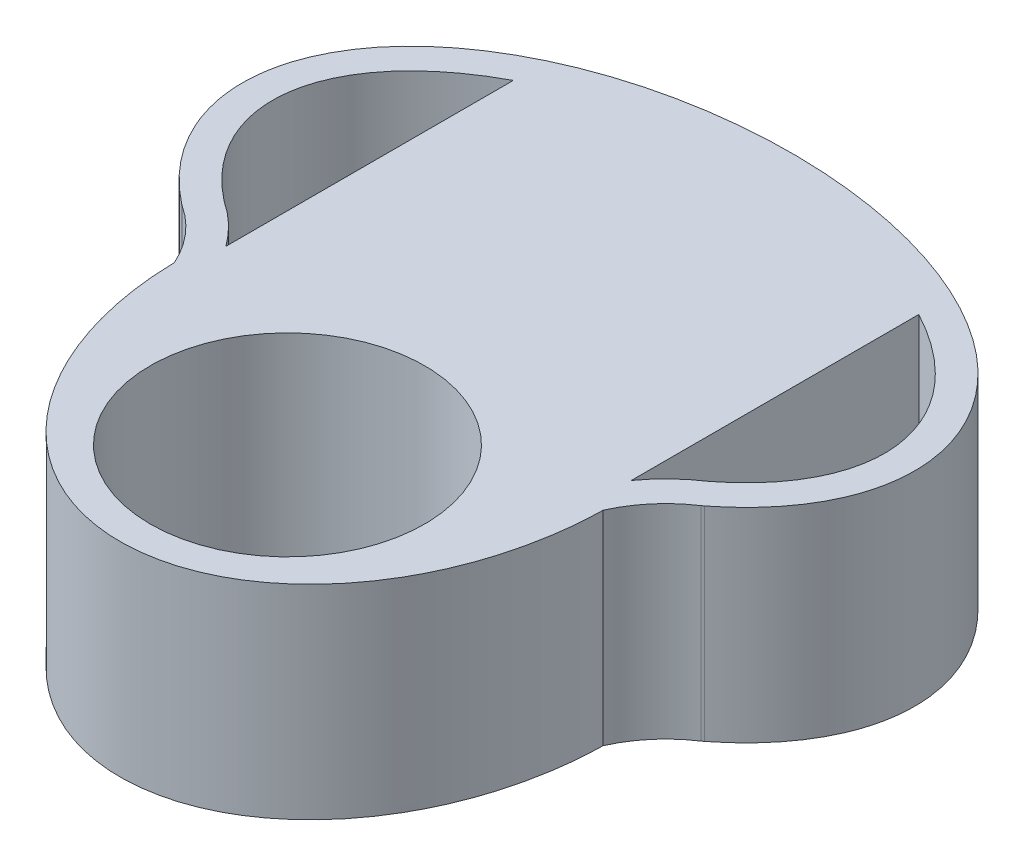
SolidWorks part; units mm, degrees
ref_plane "Front Plane" through (0, 0, 0) normal (0, 0, 1) x (1, 0, 0)
ref_plane "Top Plane" through (0, 0, 0) normal (0, 1, 0) x (1, 0, 0)
ref_plane "Right Plane" through (0, 0, 0) normal (1, 0, 0) x (0, 0, -1)
sketch "Sketch2" plane through (0, 0, 0) normal (0, 1, 0) x (1, 0, 0)
  line L0 (0, -133.35) -> (0, -153.202) construction
  line L1 (0, -153.202) -> (0, -133.35) construction
  line L2 (-81.4183, -42.1453) -> (-80.7825, -42.602)
  line L3 (81.4183, -42.1453) -> (80.7825, -42.602)
  line L6 (-63.1172, -46.6961) -> (-63.1172, 42.8014)
  line L7 (-54.373, -42.2538) -> (-54.373, 46.9235)
  line L8 (-54.373, -42.2538) -> (-54.373, -81.4864)
  line L9 (0, -260.0939) -> (0, 176.9209) construction
  line L10 (63.1172, -46.6961) -> (63.1172, 42.8014)
  line L11 (54.373, -42.2538) -> (54.373, 46.9235)
  line L12 (54.373, -42.2538) -> (54.373, -81.4864)
  line L13 (-63.1172, -46.6961) -> (63.1172, -46.6961)
  arc A0 (-57.378, -57.15) -> (-75.6222, -34.7474) centre (-101.9466, -74.8157) ccw
  arc A1 (57.378, -57.15) -> (75.6222, -34.7474) centre (101.9466, -74.8157) cw
  circle A2 centre (0, -90.6305) radius 42.7195
  arc A3 (66.759, -59.0842) -> (80.7825, -42.602) centre (101.9466, -74.8157) cw
  arc A4 (-66.759, -59.0842) -> (-80.7825, -42.602) centre (-101.9466, -74.8157) ccw
  arc A6 (66.1147, -60.613) -> (80.7825, -42.602) centre (101.9466, -74.8157) cw construction
  arc A7 (-66.1147, -60.613) -> (-80.7825, -42.602) centre (-101.9466, -74.8157) ccw construction
  ellipse E0 centre (0, 0) end of major axis (-95.25, 0) minor radius 57.15 (75.6222, -34.7474) -> (-75.6222, -34.7474) ccw
  ellipse E1 centre (0, -57.15) end of major axis (0, -133.35) minor radius 57.378 (-57.378, -57.15) -> (57.378, -57.15) ccw
  ellipse E2 centre (0, -57.15) end of major axis (0, -133.35) minor radius 57.378 (57.378, -57.15) -> (-57.378, -57.15) cw
  ellipse E3 centre (0, 0) end of major axis (95.25, 0) minor radius 57.15 (-75.6222, -34.7474) -> (75.6222, -34.7474) cw
  spline S0 degree 1 poles (-66.776, -57.15) (66.776, -57.15) knots 0 0 1 1 construction
  spline S1 degree 3 poles (-66.776, -57.15) (-66.776, -57.6322) (-66.7707, -58.4398) (-66.6753, -63.8877) (-65.7907, -74.2867) (-62.3657, -89.291) (-56.4612, -103.9799) (-45.7253, -121.3928) (-31.0376, -134.5468) (-13.7145, -141.5469) (0, -143.3486) (13.7145, -141.5469) (31.0376, -134.5468) (45.7253, -121.3928) (56.4612, -103.9799) (62.3657, -89.291) (65.7907, -74.2867) (66.6753, -63.8877) (66.7707, -58.4398) (66.776, -57.6322) (66.776, -57.15) knots -1.570796 -1.570796 -1.570796 -1.570796 -1.553375 -1.541761 -1.374447 -1.178097 -0.981748 -0.785398 -0.392699 -0.19635 0 0.19635 0.392699 0.785398 0.981748 1.178097 1.374447 1.541761 1.553375 1.570796 1.570796 1.570796 1.570796 only from (-66.759, -59.0842) to (66.759, -59.0842)
  spline S10 degree 1 poles (-81.4183, -42.1453) (81.4183, -42.1453) knots 0 0 1 1 construction
  spline S11 degree 3 poles (-81.4183, -42.1453) (-82.1709, -41.5556) (-83.6619, -40.3447) (-86.5049, -37.8589) (-89.8261, -34.6056) (-93.4024, -30.4841) (-97.5926, -24.7087) (-101.6709, -16.9948) (-104.4589, -7.1211) (-104.9354, 3.0448) (-102.4335, 16.4362) (-93.8031, 31.853) (-76.6112, 46.8727) (-54.1789, 58.0537) (-28.0504, 64.9811) (0, 67.3314) (28.0504, 64.9811) (54.1789, 58.0537) (76.6112, 46.8727) (93.8031, 31.853) (102.4335, 16.4362) (104.9354, 3.0448) (104.4589, -7.1211) (101.6709, -16.9948) (97.5926, -24.7087) (93.4024, -30.4841) (89.8261, -34.6056) (86.5049, -37.8589) (83.6619, -40.3447) (82.1709, -41.5556) (81.4183, -42.1453) knots -0.653544 -0.653544 -0.653544 -0.653544 -0.618789 -0.584034 -0.514523 -0.445012 -0.375502 -0.23648 -0.097459 0.041562 0.180583 0.458626 0.736669 1.014711 1.292754 1.570796 1.848839 2.126881 2.404924 2.682967 2.961009 3.10003 3.239052 3.378073 3.517094 3.586605 3.656116 3.725626 3.760382 3.795137 3.795137 3.795137 3.795137
  dimension "D4" = 9.398
  dimension "D1" = 114.3
  dimension "D2" = 190.5
  dimension "D3" = 152.4
  dimension "D5" = 9.398
extrude "Boss-Extrude1" add sketch "Sketch2" along normal blind 63.5 contours S11 L2 A4 S1 A3 L3 E1 A0 E0 A1 | L12 E1 A1 L10 E0 L11 | L11 E0 L7 L8 L13 L12 | A2 E1 L12 L13 L8 | A0 E1 L8 L13 | L7 E0 L6 L13 L8 | L12 E1 A1 L13
